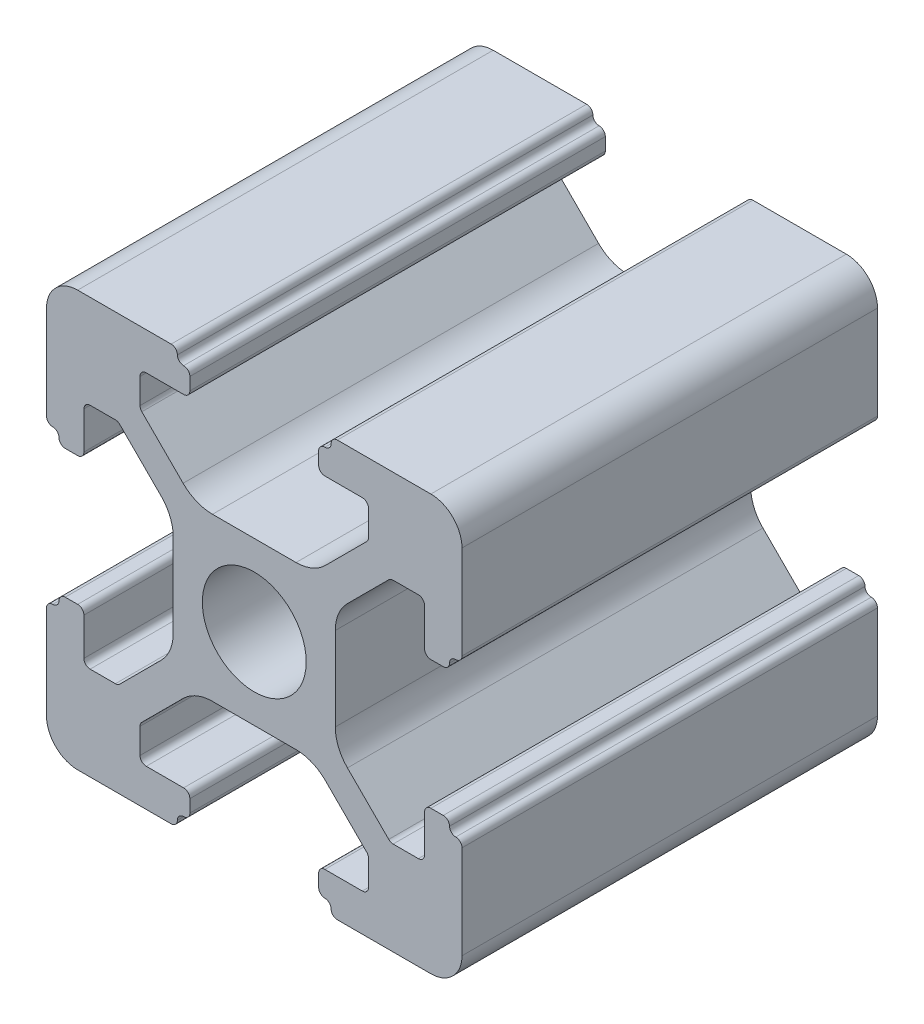
SolidWorks part; units mm, degrees
material "1060 合金"
ref_plane "前视基准面" through (0, 0, 0) normal (0, 0, 1) x (1, 0, 0)
ref_plane "上视基准面" through (0, 0, 0) normal (0, 1, 0) x (1, 0, 0)
ref_plane "右视基准面" through (0, 0, 0) normal (1, 0, 0) x (0, 0, -1)
other "Configuration Table"
sketch "草图1" plane through (0, 0, 0) normal (0, 0, 1) x (1, 0, 0)
  line L0 (-2.5, 0) -> (2.5, 0) construction
  line L1 (10, 8.5) -> (10, 4)
  line L2 (0, 2.5) -> (0, -2.5) construction
  line L3 (10, -8.5) -> (10, -4)
  line L4 (9.1, -3.1) -> (8.5, -3.1)
  line L5 (9.1, 3.1) -> (8.5, 3.1)
  line L6 (8.2, 3.4) -> (8.2, 5.2)
  line L7 (7.9, 5.5) -> (6.6849, 5.5)
  line L8 (6.4728, 5.4121) -> (4.4858, 3.4251)
  line L9 (3.9, 2.0109) -> (3.9, -2.0109)
  line L10 (0, 0) -> (10, 10) construction
  line L11 (8.2, -3.4) -> (8.2, -5.2)
  line L12 (7.9, -5.5) -> (6.6849, -5.5)
  line L13 (6.4728, -5.4121) -> (4.4858, -3.4251)
  line L14 (5.4121, 6.4728) -> (3.4251, 4.4858)
  line L15 (5.5, 7.9) -> (5.5, 6.6849)
  line L16 (3.4, 8.2) -> (5.2, 8.2)
  line L17 (3.1, 9.1) -> (3.1, 8.5)
  line L18 (8.5, 10) -> (4, 10)
  line L19 (-5.4121, 6.4728) -> (-3.4251, 4.4858)
  line L20 (-5.5, 7.9) -> (-5.5, 6.6849)
  line L21 (-3.4, 8.2) -> (-5.2, 8.2)
  line L22 (2.0109, 3.9) -> (-2.0109, 3.9)
  line L23 (-3.1, 9.1) -> (-3.1, 8.5)
  line L24 (-8.5, 10) -> (-4, 10)
  line L25 (-10, 10) -> (0, 0) construction
  line L26 (-10, 8.5) -> (-10, 4)
  line L27 (-9.1, 3.1) -> (-8.5, 3.1)
  line L28 (-3.9, -2.0109) -> (-3.9, 2.0109)
  line L29 (-8.2, 3.4) -> (-8.2, 5.2)
  line L30 (-7.9, 5.5) -> (-6.6849, 5.5)
  line L31 (-6.4728, 5.4121) -> (-4.4858, 3.4251)
  line L32 (-10, -8.5) -> (-10, -4)
  line L33 (-9.1, -3.1) -> (-8.5, -3.1)
  line L34 (-8.2, -3.4) -> (-8.2, -5.2)
  line L35 (-7.9, -5.5) -> (-6.6849, -5.5)
  line L36 (-6.4728, -5.4121) -> (-4.4858, -3.4251)
  line L37 (5.4121, -6.4728) -> (3.4251, -4.4858)
  line L38 (5.5, -7.9) -> (5.5, -6.6849)
  line L39 (3.4, -8.2) -> (5.2, -8.2)
  line L40 (-2.0109, -3.9) -> (2.0109, -3.9)
  line L41 (-5.4121, -6.4728) -> (-3.4251, -4.4858)
  line L42 (-5.5, -7.9) -> (-5.5, -6.6849)
  line L43 (-3.4, -8.2) -> (-5.2, -8.2)
  line L44 (-3.1, -9.1) -> (-3.1, -8.5)
  line L45 (3.1, -9.1) -> (3.1, -8.5)
  line L46 (8.5, -10) -> (4, -10)
  line L47 (-8.5, -10) -> (-4, -10)
  circle A0 centre (0, 0) radius 2.5
  arc A1 (4.4858, 3.4251) -> (3.9, 2.0109) centre (5.9, 2.0109) ccw
  arc A2 (10, 4) -> (9.7, 3.7) centre (9.7, 4) cw
  arc A3 (9.1, 3.1) -> (9.4, 3.4) centre (9.1, 3.4) ccw
  arc A4 (8.5, 3.1) -> (8.2, 3.4) centre (8.5, 3.4) cw
  arc A5 (8.2, 5.2) -> (7.9, 5.5) centre (7.9, 5.2) ccw
  arc A6 (6.6849, 5.5) -> (6.4728, 5.4121) centre (6.6849, 5.2) ccw
  arc A7 (9.4, 3.4) -> (9.7, 3.7) centre (9.7, 3.4) cw
  arc A8 (10, -4) -> (9.7, -3.7) centre (9.7, -4) ccw
  arc A9 (9.4, -3.4) -> (9.7, -3.7) centre (9.7, -3.4) ccw
  arc A10 (9.1, -3.1) -> (9.4, -3.4) centre (9.1, -3.4) cw
  arc A11 (8.5, -3.1) -> (8.2, -3.4) centre (8.5, -3.4) ccw
  arc A12 (8.2, -5.2) -> (7.9, -5.5) centre (7.9, -5.2) cw
  arc A13 (6.6849, -5.5) -> (6.4728, -5.4121) centre (6.6849, -5.2) cw
  arc A14 (4.4858, -3.4251) -> (3.9, -2.0109) centre (5.9, -2.0109) cw
  arc A15 (3.4, 9.4) -> (3.7, 9.7) centre (3.4, 9.7) ccw
  arc A16 (5.5, 6.6849) -> (5.4121, 6.4728) centre (5.2, 6.6849) cw
  arc A17 (5.2, 8.2) -> (5.5, 7.9) centre (5.2, 7.9) cw
  arc A18 (3.1, 8.5) -> (3.4, 8.2) centre (3.4, 8.5) ccw
  arc A19 (3.1, 9.1) -> (3.4, 9.4) centre (3.4, 9.1) cw
  arc A20 (4, 10) -> (3.7, 9.7) centre (4, 9.7) ccw
  arc A21 (-3.4251, 4.4858) -> (-2.0109, 3.9) centre (-2.0109, 5.9) ccw
  arc A22 (-5.5, 6.6849) -> (-5.4121, 6.4728) centre (-5.2, 6.6849) ccw
  arc A23 (-5.2, 8.2) -> (-5.5, 7.9) centre (-5.2, 7.9) ccw
  arc A24 (-3.1, 8.5) -> (-3.4, 8.2) centre (-3.4, 8.5) cw
  arc A25 (-3.1, 9.1) -> (-3.4, 9.4) centre (-3.4, 9.1) ccw
  arc A26 (-3.4, 9.4) -> (-3.7, 9.7) centre (-3.4, 9.7) cw
  arc A27 (-4, 10) -> (-3.7, 9.7) centre (-4, 9.7) cw
  arc A28 (3.4251, 4.4858) -> (2.0109, 3.9) centre (2.0109, 5.9) cw
  arc A29 (-4.4858, -3.4251) -> (-3.9, -2.0109) centre (-5.9, -2.0109) ccw
  arc A30 (-10, 4) -> (-9.7, 3.7) centre (-9.7, 4) ccw
  arc A31 (-9.4, 3.4) -> (-9.7, 3.7) centre (-9.7, 3.4) ccw
  arc A32 (-9.1, 3.1) -> (-9.4, 3.4) centre (-9.1, 3.4) cw
  arc A33 (-8.5, 3.1) -> (-8.2, 3.4) centre (-8.5, 3.4) ccw
  arc A34 (-8.2, 5.2) -> (-7.9, 5.5) centre (-7.9, 5.2) cw
  arc A35 (-6.6849, 5.5) -> (-6.4728, 5.4121) centre (-6.6849, 5.2) cw
  arc A36 (-4.4858, 3.4251) -> (-3.9, 2.0109) centre (-5.9, 2.0109) cw
  arc A37 (-10, -4) -> (-9.7, -3.7) centre (-9.7, -4) cw
  arc A38 (-9.1, -3.1) -> (-9.4, -3.4) centre (-9.1, -3.4) ccw
  arc A39 (-8.5, -3.1) -> (-8.2, -3.4) centre (-8.5, -3.4) cw
  arc A40 (-8.2, -5.2) -> (-7.9, -5.5) centre (-7.9, -5.2) ccw
  arc A41 (-6.6849, -5.5) -> (-6.4728, -5.4121) centre (-6.6849, -5.2) ccw
  arc A42 (-9.4, -3.4) -> (-9.7, -3.7) centre (-9.7, -3.4) cw
  arc A43 (3.4251, -4.4858) -> (2.0109, -3.9) centre (2.0109, -5.9) ccw
  arc A44 (5.5, -6.6849) -> (5.4121, -6.4728) centre (5.2, -6.6849) ccw
  arc A45 (5.2, -8.2) -> (5.5, -7.9) centre (5.2, -7.9) ccw
  arc A46 (3.1, -8.5) -> (3.4, -8.2) centre (3.4, -8.5) cw
  arc A47 (3.1, -9.1) -> (3.4, -9.4) centre (3.4, -9.1) ccw
  arc A48 (3.4, -9.4) -> (3.7, -9.7) centre (3.4, -9.7) cw
  arc A49 (4, -10) -> (3.7, -9.7) centre (4, -9.7) cw
  arc A50 (-3.4, -9.4) -> (-3.7, -9.7) centre (-3.4, -9.7) ccw
  arc A51 (-5.5, -6.6849) -> (-5.4121, -6.4728) centre (-5.2, -6.6849) cw
  arc A52 (-5.2, -8.2) -> (-5.5, -7.9) centre (-5.2, -7.9) cw
  arc A53 (-3.1, -8.5) -> (-3.4, -8.2) centre (-3.4, -8.5) ccw
  arc A54 (-3.1, -9.1) -> (-3.4, -9.4) centre (-3.4, -9.1) cw
  arc A55 (-4, -10) -> (-3.7, -9.7) centre (-4, -9.7) ccw
  arc A56 (-3.4251, -4.4858) -> (-2.0109, -3.9) centre (-2.0109, -5.9) cw
  arc A57 (-10, -8.5) -> (-8.5, -10) centre (-8.5, -8.5) ccw
  arc A58 (8.5, -10) -> (10, -8.5) centre (8.5, -8.5) ccw
  arc A59 (10, 8.5) -> (8.5, 10) centre (8.5, 8.5) ccw
  arc A60 (-10, 8.5) -> (-8.5, 10) centre (-8.5, 8.5) cw
  point P47 (3.9, 0)
  point P86 (0, 3.9)
  point P164 (-3.9, 0)
  point P165 (0, -3.9)
  dimension "D1" = 5
extrude "凸台-拉伸1" add sketch "草图1" along normal mid plane 20
